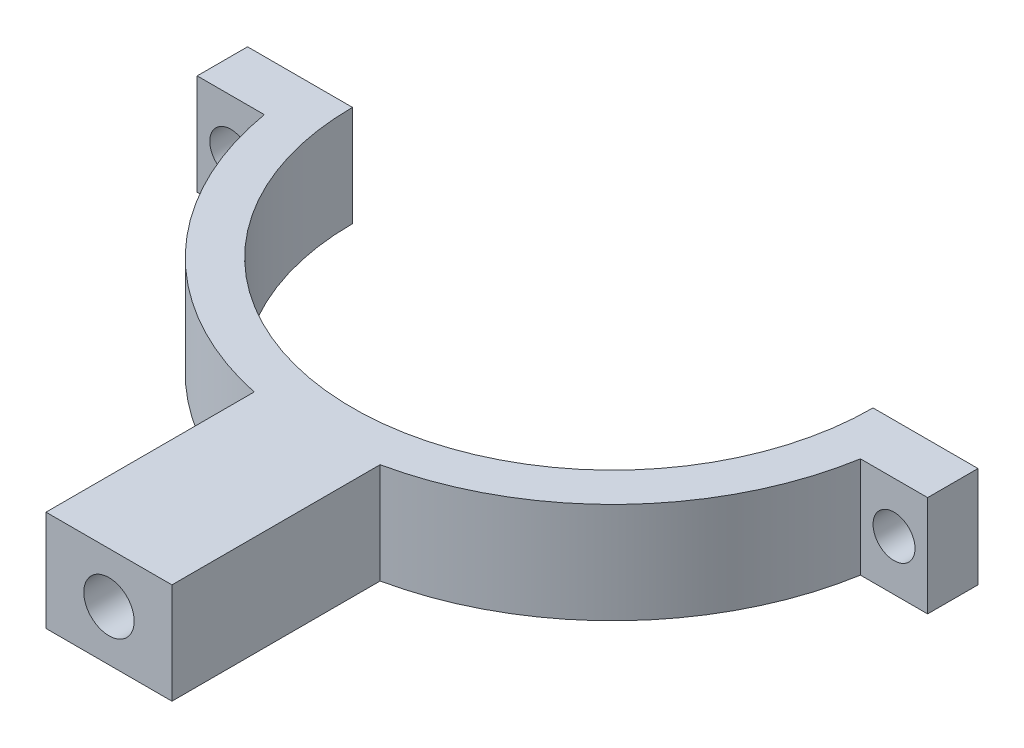
SolidWorks part; units mm, degrees
ref_plane "Front Plane" through (0, 0, 0) normal (0, 0, 1) x (1, 0, 0)
ref_plane "Top Plane" through (0, 0, 0) normal (0, 1, 0) x (1, 0, 0)
ref_plane "Right Plane" through (0, 0, 0) normal (1, 0, 0) x (0, 0, -1)
sketch "Sketch1" plane through (0, 0, 0) normal (0, 1, 0) x (1, 0, 0)
  line L0 (-39.37, 0) -> (-55.2405, 0)
  line L1 (0, 0) -> (0, -131.5058) construction
  line L2 (55.2405, 0) -> (55.2405, -7.62)
  line L3 (55.2405, -7.62) -> (45.0805, -7.62)
  line L4 (-55.2405, 0) -> (-55.2405, -7.62)
  line L5 (39.37, 0) -> (55.2405, 0)
  line L6 (-55.2405, -7.62) -> (-45.0805, -7.62)
  line L8 (-9.525, -76.2) -> (9.525, -76.2)
  line L9 (-9.525, -76.2) -> (-9.525, -44.7168)
  line L10 (9.525, -76.2) -> (9.525, -44.7168)
  arc A0 (-39.37, 0) -> (39.37, 0) centre (0, 0) ccw
  arc A1 (9.525, -44.7168) -> (45.0805, -7.62) centre (0, 0) ccw
  arc A2 (-45.0805, -7.62) -> (-9.525, -44.7168) centre (0, 0) ccw
  arc A3 (9.525, -44.7168) -> (45.0805, -7.62) centre (0, 0) ccw
  arc A4 (-45.0805, -7.62) -> (-9.525, -44.7168) centre (0, 0) ccw
  point P7 (0, -76.2)
  dimension "D1" = 45.72
  dimension "D2" = 39.37
  dimension "D6" = 76.2
  dimension "D7" = 10.16
  dimension "D4" = 10.16
  dimension "D3" = 7.62
  dimension "D5" = 19.05
extrude "Boss-Extrude1" add sketch "Sketch1" along normal blind 15.24
sketch "Sketch7" plane through (0, 0, 76.2) normal (0, 0, 1) x (1, 0, 0)
  line L0 (0, 0) -> (0, 15.24) construction
  line L1 (-9.525, 15.24) -> (9.525, 15.24) construction
  circle A0 centre (0, 7.62) radius 3.81
hole_wizard "Tap Drill for M10x1.0 Tap1" positions "Sketch12" profile "Sketch14" hole size "M10x1.0" standard "AS"
sketch "Sketch12" plane through (0, 0, 76.2) normal (0, 0, 1) x (1, 0, 0)
  point P0 (0, 7.62)
sketch "Sketch14" plane through (0, 7.62, 76.2) normal (1, 0, 0) x (0, -1, 0)
  line L0 (0, 0) -> (0, 9.9093)
  line L1 (0, 9.9093) -> (3.81, 7.62)
  line L2 (3.81, 7.62) -> (3.81, 0)
  line L5 (3.81, 0) -> (0, 0)
  line L10 (0, 9.9093) -> (-3.81, 7.62) construction
  line L11 (0, -6.35) -> (0, 107.95) construction
  dimension "Hole Dia." = 7.62
  dimension "Hole Depth" = 7.62
  dimension "Drill Angle" = 118
sketch "Sketch25" plane through (0, 0, 7.62) normal (0, 0, 1) x (1, 0, 0)
  line L0 (-50.1605, 15.24) -> (-50.1605, 7.62) construction
  line L3 (50.1605, 15.24) -> (50.1605, 7.62) construction
  line L6 (-55.2405, 15.24) -> (-45.0805, 15.24) construction
  line L7 (55.2405, 15.24) -> (45.0805, 15.24) construction
  dimension "D1" = 7.62
hole_wizard "Tap Drill for M10x1.0 Tap3" positions "Sketch27" profile "Sketch28" hole size "M10x1.0" standard "AS"
sketch "Sketch27" plane through (0, 0, 7.62) normal (0, 0, 1) x (1, 0, 0)
  point P0 (-50.1605, 7.62)
  point P3 (50.1605, 7.62)
sketch "Sketch28" plane through (-50.1605, 7.62, 7.62) normal (1, 0, 0) x (0, -1, 0)
  line L0 (0, 0) -> (0, 9.5277)
  line L1 (0, 9.5277) -> (3.175, 7.62)
  line L2 (3.175, 7.62) -> (3.175, 0)
  line L5 (3.175, 0) -> (0, 0)
  line L10 (0, 9.5277) -> (-3.175, 7.62) construction
  line L11 (0, -6.35) -> (0, 107.95) construction
  dimension "Hole Dia." = 6.35
  dimension "Hole Depth" = 7.62
  dimension "Drill Angle" = 118
